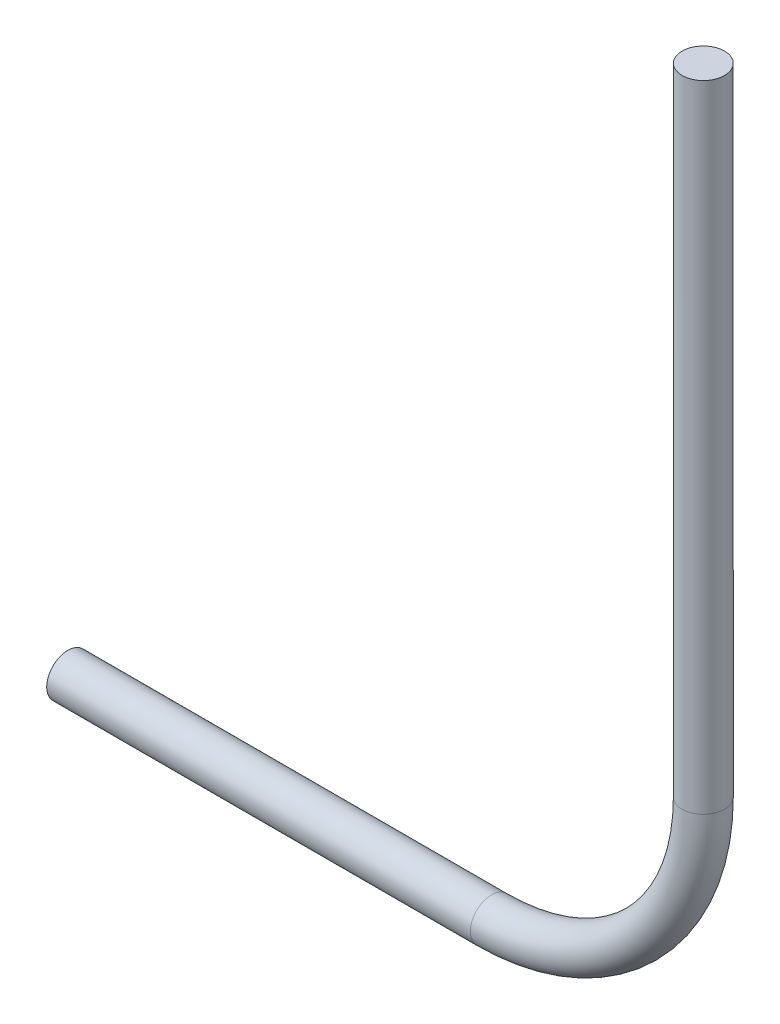
SolidWorks part; units mm, degrees
ref_plane "正面" through (0, 0, 0) normal (0, 0, 1) x (1, 0, 0)
ref_plane "平面" through (0, 0, 0) normal (0, 1, 0) x (1, 0, 0)
ref_plane "右側面" through (0, 0, 0) normal (1, 0, 0) x (0, 0, -1)
sketch "ｽｹｯﾁ1" plane through (0, 0, 0) normal (0, 0, 1) x (1, 0, 0)
  line L0 (0, 0) -> (20, 0)
  line L1 (30, 10) -> (30, 40)
  arc A0 (20, 0) -> (30, 10) centre (20, 10) ccw
  point P6 (30, 0)
  dimension "D3" = 10
  dimension "D1" = 30
  dimension "D2" = 40
sketch "ｽｹｯﾁ4" plane through (0, 0, 0) normal (1, 0, 0) x (0, 0, -1)
  circle A0 centre (0, 0) radius 1
  dimension "D1" = 2
sweep "ｽｲｰﾌﾟ1" add profiles "ｽｹｯﾁ4" path "ｽｹｯﾁ1"
